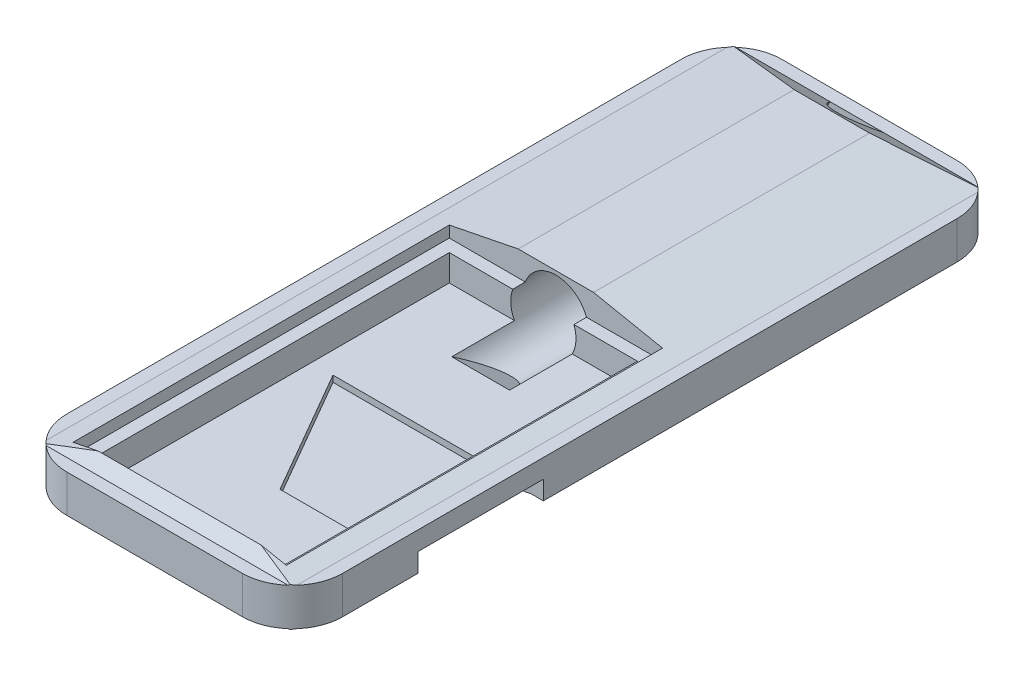
SolidWorks part; units mm, degrees
ref_plane "Спереди" through (0, 0, 0) normal (0, 0, 1) x (1, 0, 0)
ref_plane "Сверху" through (0, 0, 0) normal (0, 1, 0) x (1, 0, 0)
ref_plane "Справа" through (0, 0, 0) normal (1, 0, 0) x (0, 0, -1)
sketch "Эскиз2" plane through (0, 0, 0) normal (0, 0, 1) x (1, 0, 0)
  line L0 (-10, 1.5) -> (-3, 2.9)
  line L1 (-11, -1.5) -> (-10, -1.5)
  line L2 (-11, -1.5) -> (-11, 1.5)
  line L3 (-11, 1.5) -> (-10, 1.5)
  line L4 (11, -1.5) -> (11, 1.5)
  line L5 (-11, -1.5) -> (11, 1.5) construction
  line L6 (-11, 1.5) -> (11, -1.5) construction
  line L7 (-1000, 0) -> (49000, 0) construction
  line L8 (0, -1000) -> (0, 49000) construction
  line L9 (-3, 2.9) -> (0, 2.9)
  line L10 (3, 2.9) -> (0, 2.9)
  line L11 (10, 1.5) -> (3, 2.9)
  line L12 (-10, 1.5) -> (0, 1.5) construction
  line L13 (10, 1.5) -> (11, 1.5)
  line L14 (0, 1.5) -> (10, 1.5) construction
  line L15 (-10, -1.5) -> (-3, -2.9)
  line L16 (-3, -2.9) -> (0, -2.9)
  line L17 (3, -2.9) -> (0, -2.9)
  line L18 (10, -1.5) -> (3, -2.9)
  line L19 (-10, -1.5) -> (0, -1.5) construction
  line L20 (10, -1.5) -> (11, -1.5)
  line L21 (0, -1.5) -> (10, -1.5) construction
  point P0 (0, 0)
  dimension "D1" = 22
  dimension "D2" = 3
  dimension "D3" = 2.9
  dimension "D4" = 1
  dimension "D5" = 6
  dimension "D6" = 11.31
extrude "Бобышка-Вытянуть1" add sketch "Эскиз2" along normal mid plane 57
fillet "Скругление3" radius 4 4 edges at (-11, 0, -28.5) (-11, 0, 28.5) (11, 0, 28.5) (11, 0, -28.5)
sketch "Эскиз3" plane through (0, 0, 0) normal (1, 0, 0) x (0, 0, -1)
  line L0 (-1000, 0) -> (49000, 0) construction
  line L3 (28.5, 1.5) -> (28.5, 2.1) construction
  line L6 (28.5, 2.1) -> (28.5, 1.5) construction
  line L12 (-28.5, 2.9) -> (-25.5, 2.9)
  line L13 (28.5, 2.9) -> (28.5, 1.5)
  line L14 (28.5, 1.5) -> (27.5, 1.5)
  line L18 (-27.5, 1.5) -> (-25.5, 2.9)
  line L19 (-28.5, 2.9) -> (-28.5, 2.1)
  line L21 (0, -1000) -> (0, 49000) construction
  line L23 (-28.5, -2.1) -> (-28.5, 2.1) construction
  line L24 (-28.5, 1.5) -> (-27.5, 1.5)
  line L25 (-28.5, -2.1) -> (-28.5, 1.5)
  line L26 (-28.5, 2.9) -> (28.5, 2.9) construction
  line L29 (-28.5, 2.9) -> (28.5, 2.9)
  line L30 (-24.5, 1.5) -> (-24.5, 0) construction
  line L33 (24.5, 1.5) -> (-24.5, 1.5)
  line L34 (-24.5, 1.5) -> (-24.5, -1.5)
  line L35 (-24.5, -1.5) -> (24.5, -1.5)
  line L36 (24.5, -1.5) -> (24.5, 1.5)
  line L37 (24.5, 1.5) -> (-24.5, 1.5)
  line L38 (-24.5, 0) -> (-24.5, -1.5) construction
  line L39 (-24.5, -1.5) -> (24.5, -1.5)
  line L40 (24.5, -1.5) -> (24.5, 1.5)
  line L41 (-28.5, 2.1) -> (-28.5, 1.5) construction
  line L42 (-28.5, 1.5) -> (-28.5, 2.1) construction
  line L43 (-28.5, 2.9) -> (-28.5, 1.5)
  line L44 (28.5, 2.9) -> (28.5, 2.1)
  line L45 (27.5, 1.5) -> (25.5, 2.9)
  line L46 (28.5, 2.9) -> (25.5, 2.9)
  line L47 (-28.5, -1.5) -> (-28.5, -2.1) construction
  line L48 (-28.5, -2.1) -> (-28.5, -1.5) construction
  line L49 (-28.5, -2.9) -> (-28.5, -1.5)
  line L50 (-28.5, -1.5) -> (-27.5, -1.5)
  line L51 (-28.5, -2.9) -> (-28.5, -2.1)
  line L52 (-27.5, -1.5) -> (-25.5, -2.9)
  line L53 (-28.5, -2.9) -> (-25.5, -2.9)
  line L54 (28.5, -2.1) -> (28.5, -1.5) construction
  line L55 (28.5, -1.5) -> (28.5, -2.1) construction
  line L56 (28.5, -2.9) -> (25.5, -2.9)
  line L57 (27.5, -1.5) -> (25.5, -2.9)
  line L58 (28.5, -2.9) -> (28.5, -2.1)
  line L59 (28.5, -1.5) -> (27.5, -1.5)
  line L60 (28.5, -2.9) -> (28.5, -1.5)
  dimension "D1" = 2
  dimension "D2" = 0
  dimension "D3" = 1
extrude "Вырез-Вытянуть1" cut sketch "Эскиз3" against normal through all both and the other way through all
sketch "Эскиз4" plane through (0, 0, 0) normal (0, 1, 0) x (1, 0, 0)
  line L0 (0, -1000) -> (0, 49000) construction
  line L2 (-7.5, -26.5) -> (7.5, -26.5)
  line L3 (-7.5, -26.5) -> (-7.5, 2.5)
  line L4 (-7.5, 2.5) -> (7.5, 2.5)
  line L5 (7.5, -26.5) -> (7.5, 2.5)
  line L6 (-7.5, -26.5) -> (7.5, 2.5) construction
  line L7 (-7.5, 2.5) -> (7.5, -26.5) construction
  point P1 (0, -12)
  point P10 (0, 0)
  point P13 (4.8641, 6.2385)
  point P14 (0, -12.1154)
  point P15 (0, 0)
  dimension "D1" = 15
  dimension "D2" = 29
  dimension "D4" = 26.5
extrude "Вырез-Вытянуть5" cut sketch "Эскиз4" against normal mid plane 2.4
sketch "Эскиз5" plane through (0, 0, -2.5) normal (0, 0, 1) x (1, 0, 0)
  circle A0 centre (0, 0) radius 2.6
  dimension "D1" = 5.2
extrude "Вырез-Вытянуть6" cut sketch "Эскиз5" against normal blind 25 and the other way blind 5
sketch "Эскиз6" plane through (0, 1.2, 0) normal (0, -1, 0) x (1, 0, 0)
  line L0 (-2.3065, -2.5) -> (2.3065, -2.5)
  line L19 (-7.5, -2.5) -> (-2.3065, -2.5)
  line L24 (-2.3065, -2.5) -> (-2.3065, 2.5)
  line L25 (-2.3065, 2.5) -> (2.3065, 2.5)
  line L26 (2.3065, 2.5) -> (2.3065, -2.5)
  line L27 (2.3065, -2.5) -> (7.5, -2.5)
  line L28 (7.5, -2.5) -> (7.5, 26.5)
  line L29 (7.5, 26.5) -> (-7.5, 26.5)
  line L30 (-7.5, 26.5) -> (-7.5, -2.5)
  line L31 (-7.5, -2.5) -> (-2.3065, -2.5)
  line L35 (2.3065, -2.5) -> (7.5, -2.5)
  line L36 (7.5, -2.5) -> (7.5, 26.5)
  line L37 (7.5, 26.5) -> (-7.5, 26.5)
  line L38 (-7.5, 26.5) -> (-7.5, -2.5)
  dimension "D1" = 0
extrude "Вырез-Вытянуть7" cut sketch "Эскиз6" against normal through all
draft "Уклон1" type of draft neutral plane draft angle 60 faces to draft 1 face at (0, -1.9, 2.5) neutral plane through (0, -1.2, 0) neutral plane normal (0, 1, 0) parameters "D1"=60
sketch "Эскиз7" plane through (0, 0, 0) normal (1, 0, 0) x (0, 0, -1)
  line L0 (-28.5, -1.5) -> (-28.5, 1.5) construction
  line L1 (-28.5, -1.5) -> (-28.5, 1.5)
  line L2 (2.5, -1.2) -> (-26.5, -1.2) construction
  line L3 (-18.5, -1.7) -> (-8.5, -1.7)
  line L4 (-18.5, -1.7) -> (-18.5, 0)
  line L5 (-18.5, 0) -> (-8.5, 0)
  line L6 (-8.5, -1.7) -> (-8.5, 0)
  line L7 (-18.5, -1.7) -> (-8.5, 0) construction
  line L8 (-18.5, 0) -> (-8.5, -1.7) construction
  line L9 (2.5, -1.2) -> (-26.5, -1.2)
  point P2 (-13.5, -0.85)
  dimension "D1" = 10
  dimension "D2" = 0
  dimension "D3" = 0.5
  dimension "D4" = 10
extrude "Вырез-Вытянуть8" cut sketch "Эскиз7" along normal through all contours L9 L6 L5 L4 | L6 L9 L4 L3
draft "Уклон3" type of draft neutral plane draft angle 30 faces to draft 1 face at (0, -1.45, 13.5) neutral plane through (11, 0, 18.5) neutral plane normal (0, 0, -1) parameters "D1"=30
sketch "Эскиз8" plane through (0, 2.9, 0) normal (0, 1, 0) x (1, 0, 0)
  line L0 (3, 2.5) -> (7.5, 2.5) construction
  line L1 (-2.6, 2.5) -> (2.6, 2.5) construction
  line L2 (-2.3065, 2.5) -> (-7.5, 2.5) construction
  line L3 (-7.5, -26.5) -> (-7.5, 2.5) construction
  line L4 (7.5, 2.5) -> (7.5, -26.5) construction
  line L5 (3, 2.5) -> (7.5, 2.5) construction
  line L6 (-2.6, 2.5) -> (2.6, 2.5) construction
  line L7 (-2.3065, 2.5) -> (-7.5, 2.5) construction
  line L8 (-7.5, -26.5) -> (-7.5, 2.5) construction
  line L9 (7.5, 2.5) -> (7.5, -26.5) construction
  line L10 (-8.5, -26.5) -> (-8.5, 3.5)
  line L11 (-8.5, 3.5) -> (8.5, 3.5)
  line L12 (-2.3065, 3.5) -> (-8.5, 3.5) construction
  line L14 (8.5, 3.5) -> (8.5, -26.5)
  line L15 (-8.5, -26.5) -> (8.5, -26.5)
  line L18 (3, 3.5) -> (8.5, 3.5) construction
  dimension "D1" = 1
extrude "Вырез-Вытянуть9" cut sketch "Эскиз8" against normal blind 2
